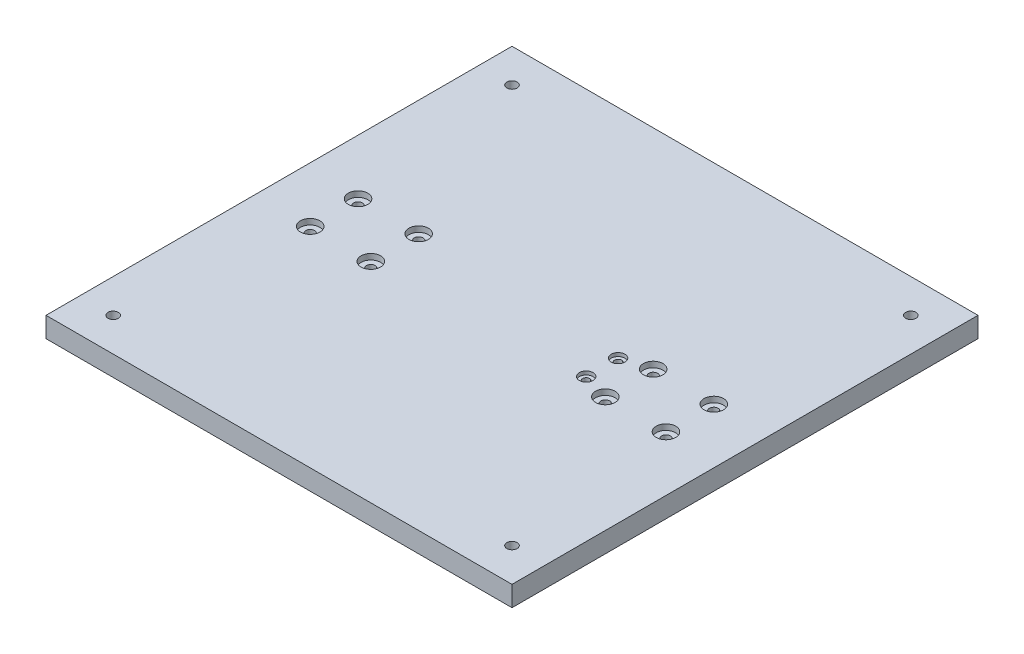
SolidWorks part; units mm, degrees
ref_plane "Front Plane" through (0, 0, 0) normal (0, 0, 1) x (1, 0, 0)
ref_plane "Top Plane" through (0, 0, 0) normal (0, 1, 0) x (1, 0, 0)
ref_plane "Right Plane" through (0, 0, 0) normal (1, 0, 0) x (0, 0, -1)
sketch "Sketch2" plane through (0, 0, 0) normal (0, 1, 0) x (1, 0, 0)
  line L1 (-146.05, -146.05) -> (146.05, -146.05)
  line L2 (-146.05, -146.05) -> (-146.05, 146.05)
  line L3 (-146.05, 146.05) -> (146.05, 146.05)
  line L4 (146.05, -146.05) -> (146.05, 146.05)
  line L5 (-146.05, -146.05) -> (146.05, 146.05) construction
  line L6 (-146.05, 146.05) -> (146.05, -146.05) construction
  point P0 (0, 0)
  dimension "D1" = 292.1
  dimension "D2" = 292.1
extrude "Boss-Extrude1" add sketch "Sketch2" along normal blind 12.7
sketch "Sketch4" plane through (0, 12.7, 0) normal (0, 1, 0) x (1, 0, 0)
  line L1 (-125, -125) -> (125, -125)
  line L2 (-125, -125) -> (-125, 125)
  line L4 (-125, 125) -> (125, 125)
  line L5 (125, -125) -> (125, 125)
  line L6 (-125, -125) -> (125, 125) construction
  line L7 (-125, 125) -> (125, -125) construction
  point P0 (0, 0)
  dimension "D1" = 250
  dimension "D2" = 250
hole_wizard "Ø6.5 (6.5) Diameter Hole1" positions "Sketch7" profile "Sketch6" hole size "Ø6.5" standard "ANSI Metric" end condition through all
sketch "Sketch7" plane through (0, 12.7, 0) normal (0, 1, 0) x (1, 0, 0)
  point P0 (-125, 125)
  point P3 (125, 125)
  point P6 (125, -125)
  point P9 (-125, -125)
sketch "Sketch6" plane through (-125, 12.7, -125) normal (1, 0, 0) x (0, 0, 1)
  line L0 (0, 0) -> (0, 12.7)
  line L1 (0, 12.7) -> (3.25, 12.7)
  line L2 (3.25, 12.7) -> (3.25, 0)
  line L5 (3.25, 0) -> (0, 0)
  line L11 (0, -6.35) -> (0, 107.95) construction
  dimension "Thru Hole Dia." = 6.5
  dimension "Thru Hole Depth" = 12.7
hole_wizard "CBORE for M5 Hex Head Bolt1" positions "Sketch11" profile "Sketch10" counterbore size "M5" standard "ANSI Metric" end condition through all
sketch "Sketch11" plane through (0, 12.7, 0) normal (0, 1, 0) x (1, 0, 0)
  line L3 (-111.5, 15) -> (-73.5, 15)
  line L4 (-111.5, 15) -> (-111.5, -15)
  line L5 (-111.5, -15) -> (-73.5, -15)
  line L6 (-73.5, 15) -> (-73.5, -15)
  line L7 (-111.5, 15) -> (-73.5, -15) construction
  line L8 (-111.5, -15) -> (-73.5, 15) construction
  line L11 (-146.05, 146.05) -> (-146.05, -146.05) construction
  line L13 (-146.05, -146.05) -> (146.05, -146.05) construction
  point P23 (-73.5, -15)
  point P90 (-111.5, 15)
  point P91 (-111.5, -15)
  point P92 (-73.5, 15)
  dimension "D1" = 30
  dimension "D2" = 38
  dimension "D3" = 131.05
  dimension "D4" = 34.55
sketch "Sketch10" plane through (-73.5, 12.7, 15) normal (1, 0, 0) x (0, 0, 1)
  line L0 (0, 0) -> (0, 12.7)
  line L1 (0, 12.7) -> (2.75, 12.7)
  line L3 (2.75, 12.7) -> (2.75, 3.58)
  line L4 (2.75, 3.58) -> (6.12, 3.58)
  line L5 (6.12, 3.58) -> (6.12, 0)
  line L7 (6.12, 0) -> (0, 0)
  line L11 (0, -6.35) -> (0, 107.95) construction
  dimension "Thru Hole Dia." = 5.5
  dimension "Thru Hole Depth" = 12.7
  dimension "C'Bore Dia." = 12.24
  dimension "C'Bore Depth" = 3.58
mirror "Mirror1" about plane through (0, 0, 0) normal (1, 0, 0) of "CBORE for M5 Hex Head Bolt1"
sketch "Sketch14" plane through (0, 0, 0) normal (0, -1, 0) x (1, 0, 0)
  line L0 (44, 10) -> (69, 10)
  line L1 (69, 10) -> (69, -10)
  line L2 (69, -10) -> (44, -10)
  point P4 (56.5, -10)
  point P9 (56.5, 10)
sketch "Sketch19" plane through (0, 12.7, 0) normal (0, 1, 0) x (1, 0, 0)
  point P0 (56.5, 10)
  point P1 (56.5, -10)
hole_wizard "CBORE for M4 SBHCS1" positions "Sketch21" profile "Sketch20" counterbore size "M4" standard "ANSI Metric" end condition through all
sketch "Sketch21" plane through (0, 12.7, 0) normal (0, 1, 0) x (1, 0, 0)
  point P0 (56.5, 10)
  point P3 (56.5, -10)
sketch "Sketch20" plane through (56.5, 12.7, -10) normal (1, 0, 0) x (0, 0, 1)
  line L0 (0, 0) -> (0, 12.7)
  line L1 (0, 12.7) -> (2.25, 12.7)
  line L3 (2.25, 12.7) -> (2.25, 2.2)
  line L4 (2.25, 2.2) -> (4.3, 2.2)
  line L5 (4.3, 2.2) -> (4.3, 0)
  line L7 (4.3, 0) -> (0, 0)
  line L11 (0, -6.35) -> (0, 107.95) construction
  dimension "Thru Hole Dia." = 4.5
  dimension "Thru Hole Depth" = 12.7
  dimension "C'Bore Dia." = 8.6
  dimension "C'Bore Depth" = 2.2
